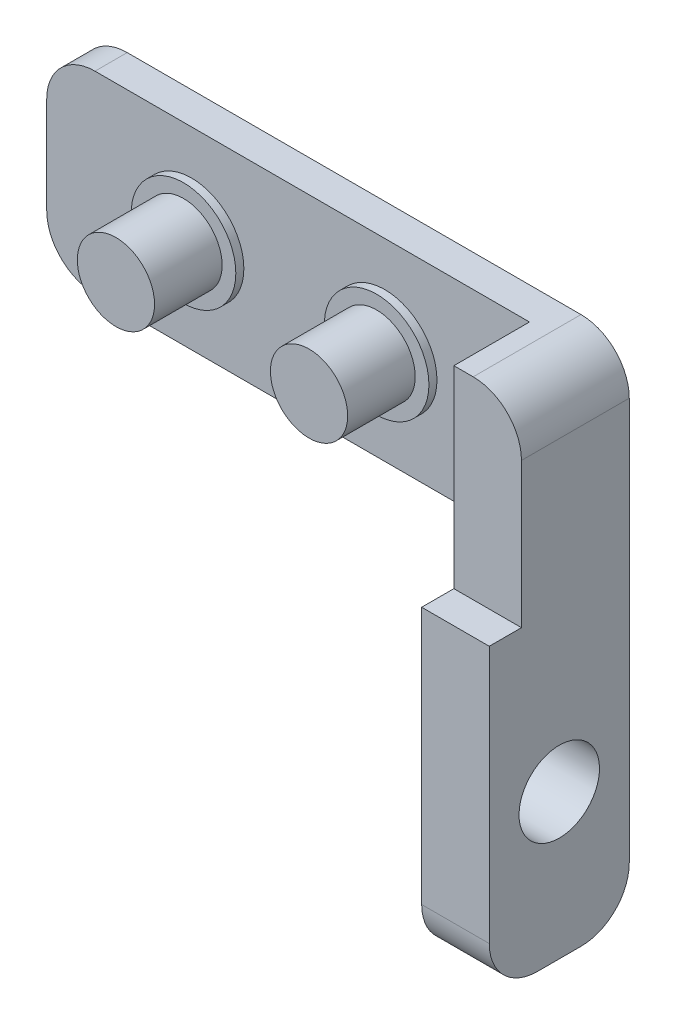
SolidWorks part; units mm, degrees
ref_plane "Plan de face" through (0, 0, 0) normal (0, 0, 1) x (1, 0, 0)
ref_plane "Plan de dessus" through (0, 0, 0) normal (0, 1, 0) x (1, 0, 0)
ref_plane "Plan de droite" through (0, 0, 0) normal (1, 0, 0) x (0, 0, -1)
sketch "Esquisse1" plane through (0, 0, 0) normal (0, 0, 1) x (1, 0, 0)
  line L1 (-12.8093, 4.9765) -> (17.1907, 4.9765)
  line L2 (-12.8093, 4.9765) -> (-12.8093, -7.0235)
  line L3 (-12.8093, -7.0235) -> (17.1907, -7.0235)
  line L4 (17.1907, 4.9765) -> (17.1907, -7.0235)
  dimension "D1" = 30
  dimension "D2" = 12
extrude "Boss.-Extru.1" add sketch "Esquisse1" along normal blind 2
sketch "Esquisse2" plane through (0, 0, 2) normal (0, 0, 1) x (1, 0, 0)
  line L0 (-6.0066, 4.9765) -> (-6.0066, -7.0235) construction
  line L1 (17.1907, 4.9765) -> (-12.8093, 4.9765) construction
  line L2 (-12.8093, -7.0235) -> (17.1907, -7.0235) construction
  line L3 (-3.8093, -1.0235) -> (8.1907, -1.0235) construction
  circle A0 centre (8.1907, -1.0235) radius 3.25
  circle A1 centre (-3.8093, -1.0235) radius 3.25
  point P10 (-6.0066, -1.0235)
  point P11 (2.1907, -1.0235)
  point P13 (2.1907, 4.9765)
  dimension "D1" = 6.5
  dimension "D2" = 12
extrude "Boss.-Extru.2" add sketch "Esquisse2" along normal blind 0.5
sketch "Esquisse3" plane through (0, 0, 2.5) normal (0, 0, 1) x (1, 0, 0)
  circle A0 centre (-3.8093, -1.0235) radius 2.4
  circle A1 centre (8.1907, -1.0235) radius 2.4
  dimension "D1" = 4.8
extrude "Boss.-Extru.3" add sketch "Esquisse3" along normal blind 4.2
sketch "Esquisse4" plane through (0, 0, 6.7) normal (0, 0, 1) x (1, 0, 0)
  circle A0 centre (8.1907, -1.0235) radius 5
  circle A1 centre (-3.8093, -1.0235) radius 5
  dimension "D1" = 10
sketch "Esquisse6" plane through (17.1907, 0, 0) normal (1, 0, 0) x (0, 0, -1)
  line L1 (0, 4.9765) -> (-6.7, 4.9765)
  line L2 (0, 4.9765) -> (0, -26.0235)
  line L3 (0, -26.0235) -> (-6.7, -26.0235)
  line L4 (-6.7, 4.9765) -> (-6.7, -26.0235)
  dimension "D1" = 19
extrude "Boss.-Extru.4" add sketch "Esquisse6" along normal blind 4.2
sketch "Esquisse8" plane through (0, 0, 6.7) normal (0, 0, 1) x (1, 0, 0)
  line L0 (21.3907, 4.9765) -> (21.3907, -26.0235) construction
  line L1 (17.1907, -26.0235) -> (21.3907, -26.0235)
  line L2 (17.1907, -26.0235) -> (17.1907, -7.0235)
  line L3 (17.1907, -7.0235) -> (21.3907, -7.0235)
  line L4 (21.3907, -26.0235) -> (21.3907, -7.0235)
extrude "Boss.-Extru.5" add sketch "Esquisse8" along normal blind 2
sketch "Esquisse9" plane through (17.1907, 0, 0) normal (-1, 0, 0) x (0, 0, 1)
  line L0 (8.7, -26.0235) -> (0, -26.0235) construction
  circle A0 centre (4.35, -17.0235) radius 2.5
  point P5 (4.35, -26.0235)
  dimension "D1" = 5
  dimension "D2" = 9
extrude "Enlèv. mat.-Extru.1" cut sketch "Esquisse9" against normal up to vertex (4.2 mm away)
fillet "Congé1" radius 3 5 edges at (21.3907, 4.9765, 3.35) (-12.8093, 4.9765, 1) (-12.8093, -7.0235, 1) (19.2907, -26.0235, 0) (19.2907, -26.0235, 8.7)
